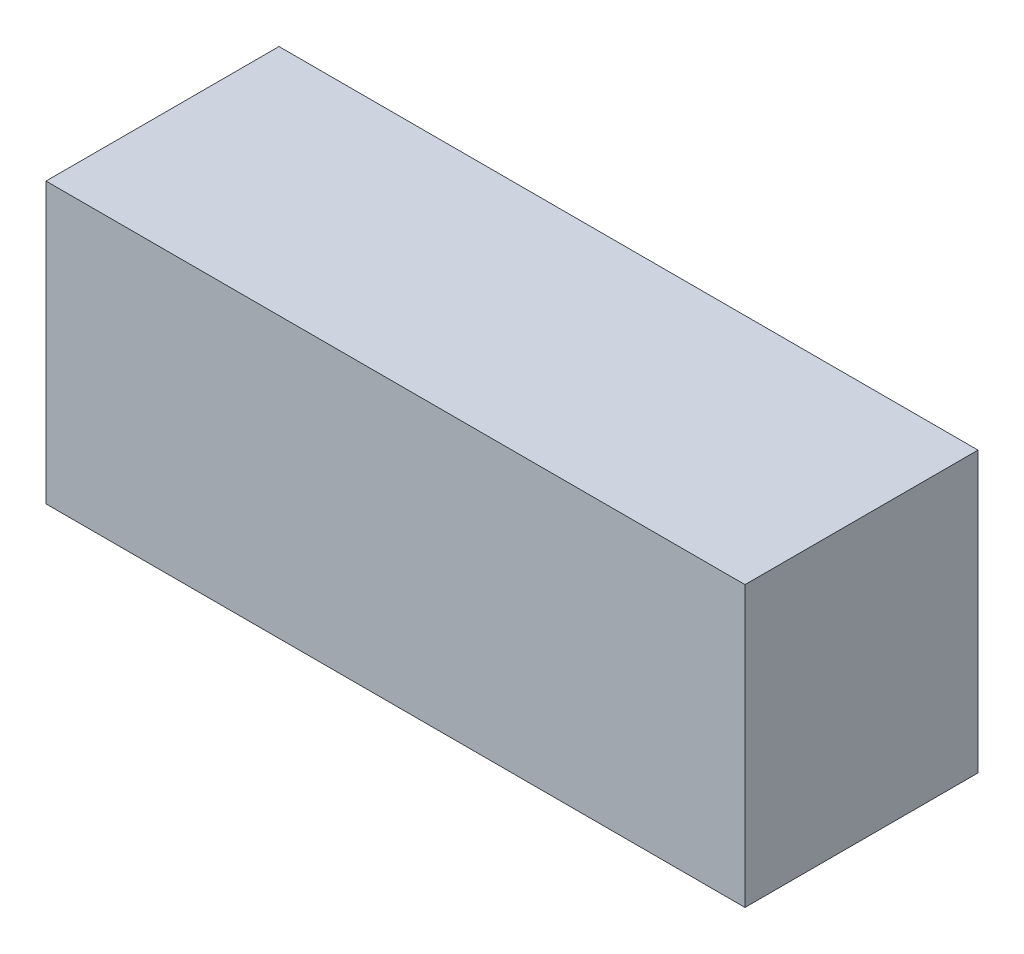
SolidWorks part; units mm, degrees
ref_plane "Front Plane" through (0, 0, 0) normal (0, 0, 1) x (1, 0, 0)
ref_plane "Top Plane" through (0, 0, 0) normal (0, 1, 0) x (1, 0, 0)
ref_plane "Right Plane" through (0, 0, 0) normal (1, 0, 0) x (0, 0, -1)
sketch "Sketch1" plane through (0, 0, 0) normal (0, 1, 0) x (1, 0, 0)
  line L1 (19.05, -6.35) -> (-19.05, -6.35)
  line L2 (19.05, -6.35) -> (19.05, 6.35)
  line L3 (19.05, 6.35) -> (-19.05, 6.35)
  line L4 (-19.05, -6.35) -> (-19.05, 6.35)
  line L5 (19.05, -6.35) -> (-19.05, 6.35) construction
  line L6 (19.05, 6.35) -> (-19.05, -6.35) construction
  point P0 (0, 0)
  dimension "D1" = 38.1
  dimension "D2" = 12.7
extrude "Boss-Extrude1" add sketch "Sketch1" along normal blind 15.24
